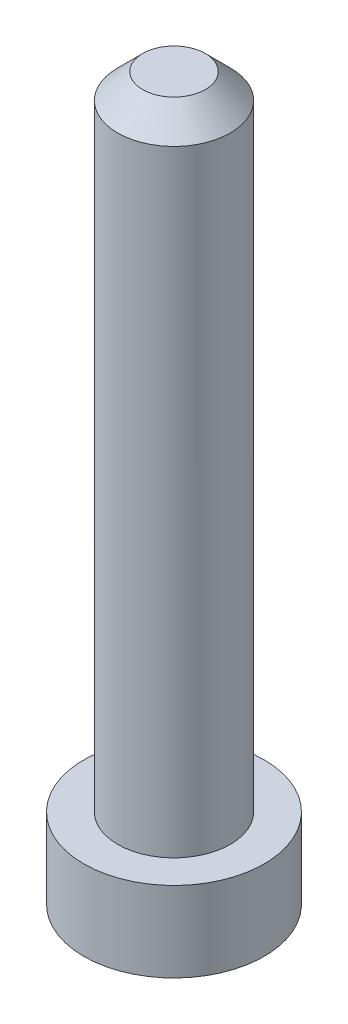
SolidWorks part; units mm, degrees
ref_plane "Front Plane" through (0, 0, 0) normal (0, 0, 1) x (1, 0, 0)
ref_plane "Top Plane" through (0, 0, 0) normal (0, 1, 0) x (1, 0, 0)
ref_plane "Right Plane" through (0, 0, 0) normal (1, 0, 0) x (0, 0, -1)
sketch "Sketch1" plane through (0, 0, 0) normal (0, 0, 1) x (1, 0, 0)
  line L0 (0, 0) -> (0, 51.9079) construction
  line L1 (0.9144, 0.8128) -> (0.5715, 0.8128)
  line L2 (0.9144, 0) -> (0.9144, 0.8128)
  line L3 (0.9144, 0) -> (0, 0)
  line L4 (0.5715, 0.8128) -> (0.5715, 7.3152)
  line L5 (0.5715, 7.3152) -> (0, 7.3152)
  line L6 (0, 7.3152) -> (0, 0)
  line L7 (0, 0) -> (0, 10.2906) construction
  dimension "D1" = 7.3152
  dimension "D2" = 0.8128
  dimension "D3" = 0.9144
  dimension "D4" = 0.5715
revolve "Revolve1" add sketch "Sketch1" angle 360 about L6
chamfer "Chamfer1" distance 0.254 angle 45 1 edges at (0, 7.3152, 0.5715)
